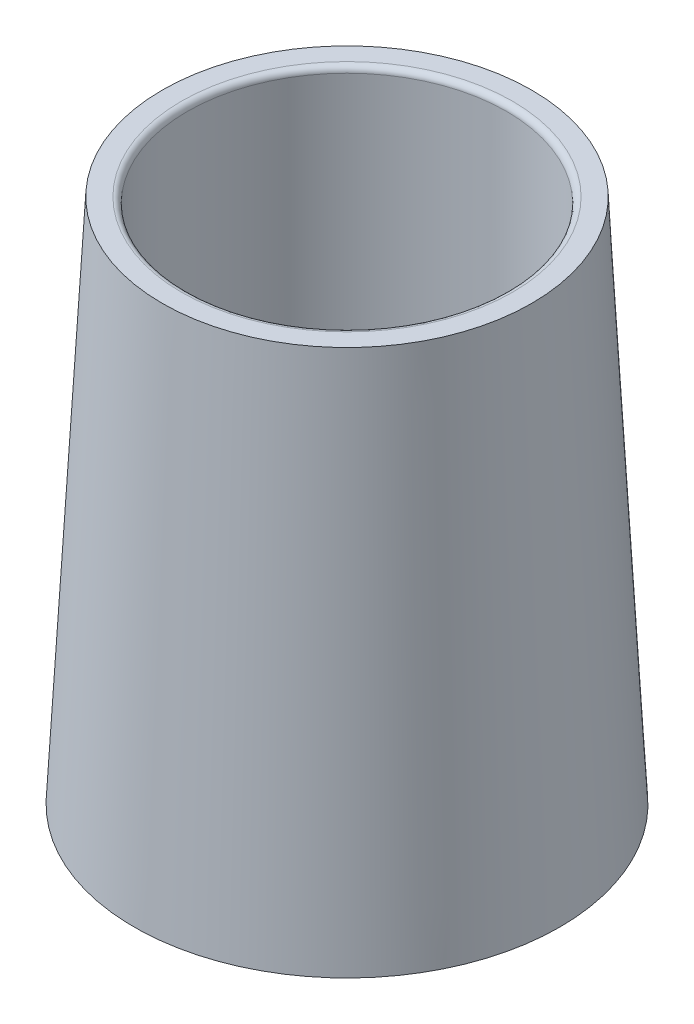
SolidWorks part; units mm, degrees
ref_plane "前基準面" through (0, 0, 0) normal (0, 0, 1) x (1, 0, 0)
ref_plane "上基準面" through (0, 0, 0) normal (0, 1, 0) x (1, 0, 0)
ref_plane "右基準面" through (0, 0, 0) normal (1, 0, 0) x (0, 0, -1)
sketch "草圖1" plane through (0, 0, 0) normal (0, 0, 1) x (1, 0, 0)
  line L0 (0, 0) -> (36, 0)
  line L1 (36, 0) -> (31.25, 89)
  line L2 (31.25, 89) -> (0, 89)
  line L3 (0, 89) -> (0, 0)
  dimension "D1" = 31.25
  dimension "D2" = 36
  dimension "D3" = 89
revolve "旋轉1" add sketch "草圖1" angle 360 about L3
sketch "草圖2" plane through (0, 89, 0) normal (0, 1, 0) x (1, 0, 0)
  circle A0 centre (0, 0) radius 27
  dimension "D1" = 54
extrude "除料-伸長1" cut sketch "草圖2" against normal blind 57
sketch "草圖3" plane through (0, 0, 0) normal (0, -1, 0) x (1, 0, 0)
  circle A0 centre (0, 0) radius 28.9
  dimension "D1" = 57.8
extrude "除料-伸長2" cut sketch "草圖3" against normal blind 11
sketch "草圖4" plane through (0, 11, 0) normal (0, -1, 0) x (1, 0, 0)
  circle A0 centre (0, 0) radius 23
  dimension "D1" = 46
extrude "除料-伸長3" cut sketch "草圖4" against normal through all
ref_plane "平面1" through (0, 0, 49.8) normal (0, 0, 1) x (1, 0, 0)
fillet "圓角1" radius 1 1 edges at (-27, 89, 0)
fillet "圓角3" radius 1 2 edges at (-23, 32, 0) (23, 11, 0)
